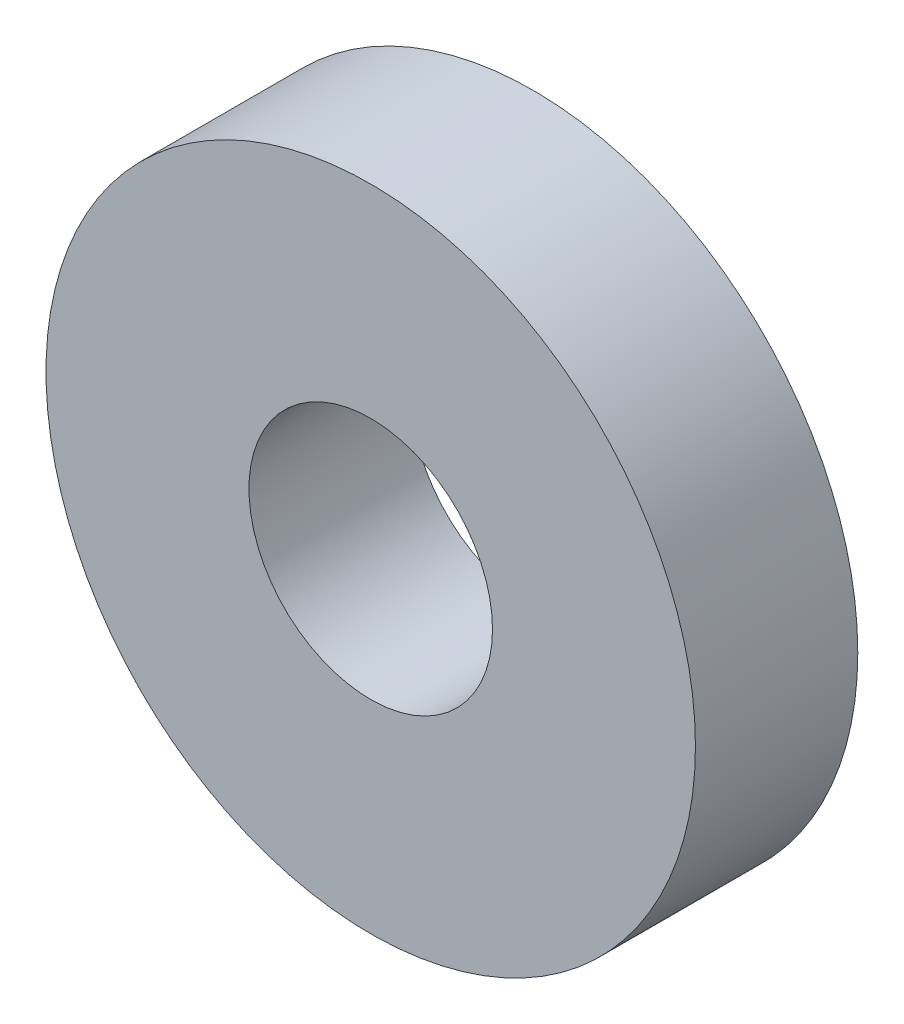
SolidWorks part; units mm, degrees
ref_plane "前视基准面" through (0, 0, 0) normal (0, 0, 1) x (1, 0, 0)
ref_plane "上视基准面" through (0, 0, 0) normal (0, 1, 0) x (1, 0, 0)
ref_plane "右视基准面" through (0, 0, 0) normal (1, 0, 0) x (0, 0, -1)
other "Configuration Table"
sketch "草图8" plane through (0, 0, 0) normal (0, 0, 1) x (1, 0, 0)
  circle A0 centre (0, 0) radius 40
  circle A1 centre (0, 0) radius 15
extrude "凸台-拉伸1" add sketch "草图8" along normal blind 20
